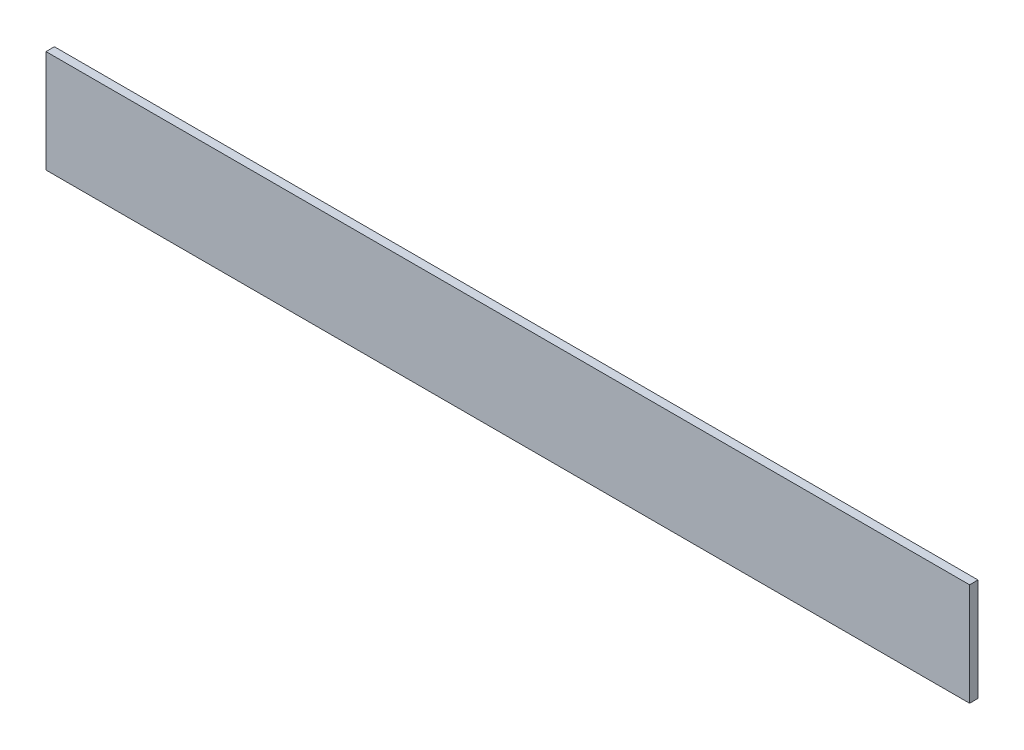
SolidWorks part; units mm, degrees
material "Beech"
ref_plane "Front Plane" through (0, 0, 0) normal (0, 0, 1) x (1, 0, 0)
ref_plane "Top Plane" through (0, 0, 0) normal (0, 1, 0) x (1, 0, 0)
ref_plane "Right Plane" through (0, 0, 0) normal (1, 0, 0) x (0, 0, -1)
sketch "Sketch1" plane through (0, 0, 0) normal (0, 1, 0) x (1, 0, 0)
  line L1 (0, 0) -> (4500, 0)
  line L2 (0, 0) -> (0, 41)
  line L3 (0, 41) -> (4500, 41)
  line L4 (4500, 0) -> (4500, 41)
  dimension "D1" = 4500
  dimension "D2" = 41
extrude "Boss-Extrude1" add sketch "Sketch1" along normal blind 500
